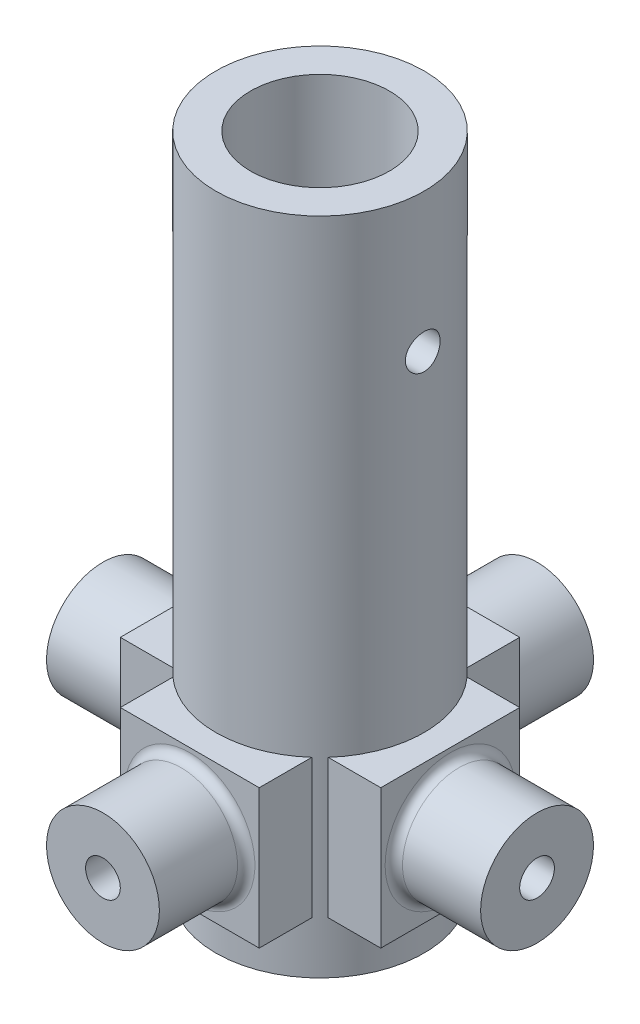
SolidWorks part; units mm, degrees
ref_plane "Front Plane" through (0, 0, 0) normal (0, 0, 1) x (1, 0, 0)
ref_plane "Top Plane" through (0, 0, 0) normal (0, 1, 0) x (1, 0, 0)
ref_plane "Right Plane" through (0, 0, 0) normal (1, 0, 0) x (0, 0, -1)
sketch "Sketch1" plane through (0, 0, 0) normal (0, 1, 0) x (1, 0, 0)
  circle A0 centre (0, 0) radius 60
  dimension "D1" = 120
extrude "Boss-Extrude1" add sketch "Sketch1" along normal blind 380
sketch "Sketch2" plane through (0, 380, 0) normal (0, 1, 0) x (1, 0, 0)
  circle A0 centre (0, 0) radius 40
  dimension "D1" = 80
extrude "Cut-Extrude1" cut sketch "Sketch2" against normal blind 300
sketch "Sketch3" plane through (0, 0, 0) normal (1, 0, 0) x (0, 0, -1)
  line L0 (0, 0) -> (0, 380) construction
  line L1 (60, 380) -> (-60, 380) construction
  circle A0 centre (0, 300) radius 10
  dimension "D1" = 20
  dimension "D2" = 300
extrude "Cut-Extrude2" cut sketch "Sketch3" against normal mid plane 300
sketch "Sketch4" plane through (0, 0, 0) normal (0, -1, 0) x (1, 0, 0)
  line L0 (75, 40) -> (-75, 40)
  line L1 (-40, 75) -> (40, 75)
  line L2 (-40, 75) -> (-40, -75)
  line L3 (-40, -75) -> (40, -75)
  line L4 (40, 75) -> (40, -75)
  line L5 (75, 40) -> (75, -40)
  line L6 (75, -40) -> (-75, -40)
  line L7 (-75, 40) -> (-75, -40)
  line L8 (40, -75) -> (40, 75)
  line L9 (40, -75) -> (-40, -75)
  line L10 (-40, -75) -> (-40, 75)
  line L11 (40, 75) -> (-40, 75)
  line L12 (-75, -40) -> (75, -40)
  line L13 (-75, -40) -> (-75, 40)
  line L14 (-75, 40) -> (75, 40)
  line L15 (75, -40) -> (75, 40)
  point P20 (0, 0)
  circle M9 centre (0, 0) radius 60
  dimension "D1" = 150
  dimension "D2" = 80
  dimension "D3" = 40
  dimension "D4" = 75
extrude "Boss-Extrude2" add sketch "Sketch4" against normal blind 80 from offset 30 contours L4 L1 L2 M9 | L0 L7 L6 M9 | L6 L4 L0 L2 | L4 L2 L3 M9 offset against normal yes
sketch "Sketch5" plane through (-75, 0, 0) normal (-1, 0, 0) x (0, 0, 1)
  line L0 (0, 30) -> (0, 110) construction
  line L1 (-40, 30) -> (40, 30) construction
  line L2 (40, 110) -> (-40, 110) construction
  circle A0 centre (0, 70) radius 32.5
  circle A1 centre (0, 70) radius 10
  dimension "D1" = 65
  dimension "D2" = 20
extrude "Boss-Extrude3" add sketch "Sketch5" along normal blind 50
fillet "Fillet1" radius 5 1 edges at (-75, 70, 32.5)
pattern_circular "CirPattern2" count 4 over 360 about axis through (0, 0, 0) along (0, 1, 0) of "Boss-Extrude3"
fillet "Fillet2" radius 5 3 edges at (-32.5, 70, -75) (75, 70, 32.5) (-32.5, 70, 75)
